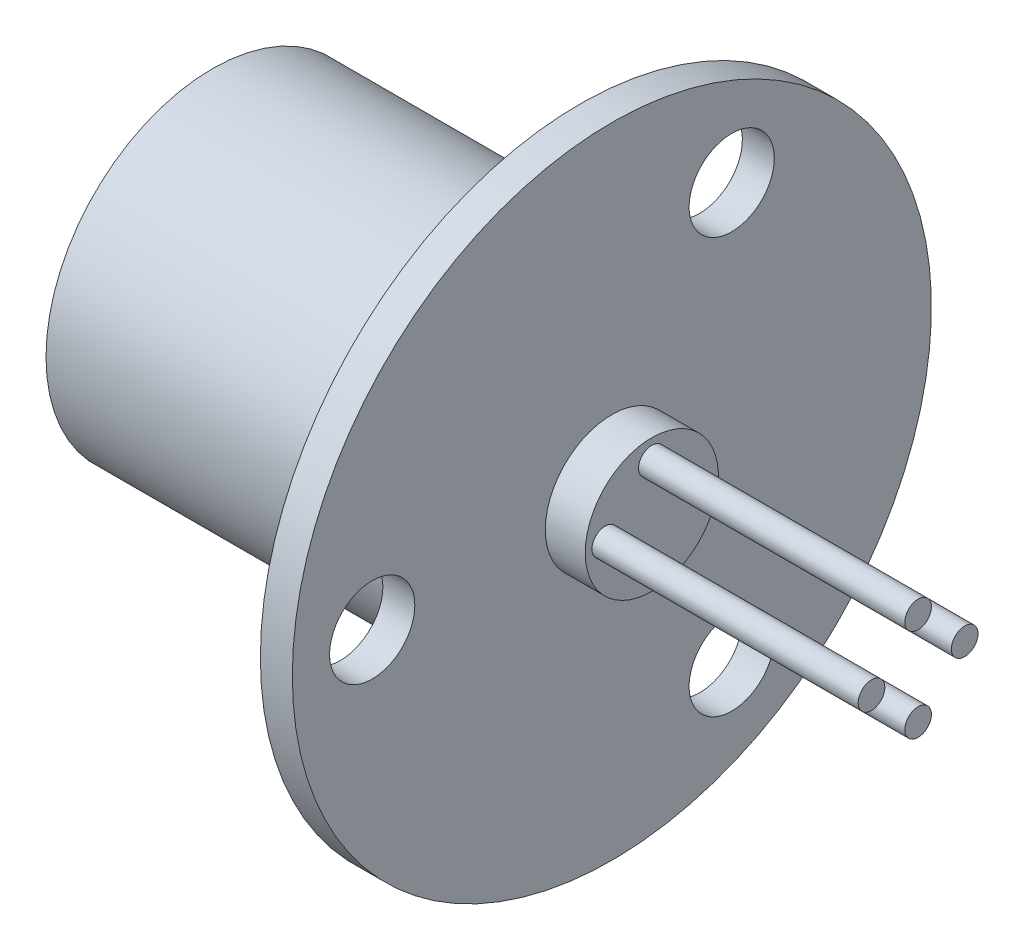
SolidWorks part; units mm, degrees
ref_plane "Alzado" through (0, 0, 0) normal (1, 0, 0) x (0, 1, 0)
ref_plane "Planta" through (0, 0, 0) normal (0, 0, 1) x (0, 1, 0)
ref_plane "Vista lateral" through (0, 0, 0) normal (0, 1, 0) x (-1, 0, 0)
sketch "Croquis1" plane through (0, 0, 0) normal (0, 1, 0) x (-1, 0, 0)
  line L0 (0, 0) -> (-26.8939, 0) construction
  line L2 (0, 0) -> (-13.8, 0)
  line L3 (0, 0) -> (0, 6.25)
  line L4 (0, 6.25) -> (-13.8, 6.25)
  line L5 (-13.8, 0) -> (-13.8, 6.25)
  line L6 (-13.8, 0) -> (-15, 0)
  line L7 (-13.8, 0) -> (-13.8, 12)
  line L8 (-13.8, 12) -> (-15, 12)
  line L9 (-15, 0) -> (-15, 12)
  line L10 (-15, 0) -> (-16.5, 0)
  line L11 (-15, 0) -> (-15, 2.5)
  line L12 (-15, 2.5) -> (-16.5, 2.5)
  line L13 (-16.5, 0) -> (-16.5, 2.5)
  dimension "D1" = 6.25
  dimension "D2" = 12
  dimension "D3" = 1.2
  dimension "D4" = 15
  dimension "D5" = 1.5
  dimension "D6" = 2.5
revolve "Revolución1" add sketch "Croquis1" angle 360 about L0
sketch "Croquis2" plane through (15, 0, 0) normal (1, 0, 0) x (0, 1, 0)
  circle A0 centre (0, 0) radius 9 construction
  circle A1 centre (0, 9) radius 1.6
  dimension "D1" = 18
  dimension "D2" = 3.2
extrude "Cortar-Extruir1" cut sketch "Croquis2" against normal blind 3.2
pattern_circular "MatrizC1" count 3 over 360 about axis through (0, 0, 0) along (1, 0, 0) of "Cortar-Extruir1"
sketch "Croquis3" plane through (16.5, 0, 0) normal (1, 0, 0) x (0, 1, 0)
  circle A0 centre (0, 0) radius 1.75 construction
  circle A1 centre (0, 1.75) radius 0.5
  dimension "D1" = 3.5
  dimension "D2" = 1
extrude "Saliente-Extruir1" add sketch "Croquis3" along normal blind 10
pattern_circular "MatrizC2" count 4 over 360 about axis through (0, 0, 0) along (1, 0, 0) of "Saliente-Extruir1"
